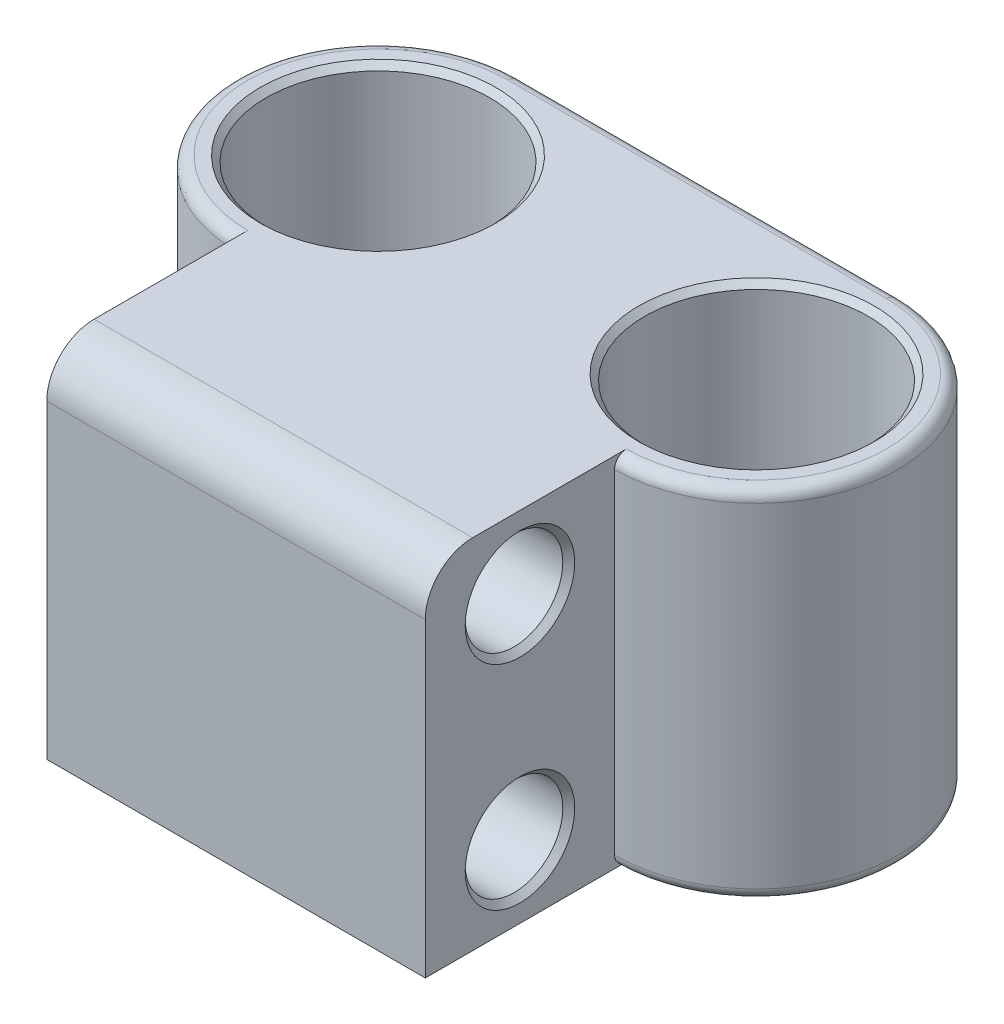
SolidWorks part; units mm, degrees
ref_plane "Front Plane" through (0, 0, 0) normal (0, 0, 1) x (1, 0, 0)
ref_plane "Top Plane" through (0, 0, 0) normal (0, 1, 0) x (1, 0, 0)
ref_plane "Right Plane" through (0, 0, 0) normal (1, 0, 0) x (0, 0, -1)
sketch "Sketch1" plane through (0, 0, 0) normal (0, 1, 0) x (1, 0, 0)
  line L0 (-12.7, 15.875) -> (12.7, 15.875) construction
  line L1 (12.7, -6.35) -> (-12.7, -6.35)
  line L2 (12.7, -6.35) -> (12.7, 6.35)
  line L4 (-12.7, -6.35) -> (-12.7, 6.35)
  line L5 (12.7, -6.35) -> (-12.7, 6.35) construction
  line L6 (12.7, 6.35) -> (-12.7, -6.35) construction
  line L7 (0, 15.875) -> (0, 0) construction
  line L9 (12.7, 25.4) -> (-12.7, 25.4)
  circle A0 centre (-12.7, 15.875) radius 7.5
  arc A1 (-12.7, 25.4) -> (-12.7, 6.35) centre (-12.7, 15.875) ccw
  circle A2 centre (12.7, 15.875) radius 7.5
  arc A3 (12.7, 25.4) -> (12.7, 6.35) centre (12.7, 15.875) cw
  point P0 (0, 0)
  dimension "D3" = 15
  dimension "D1" = 12.7
  dimension "D2" = 25.4
  dimension "D4" = 25.4
  dimension "D5" = 15.875
  dimension "D6" = 25.4
extrude "Boss-Extrude1" add sketch "Sketch1" along normal blind 24
fillet "Fillet1" [suppressed] radius 3.175
chamfer "Chamfer1" distance 0.4 angle 45 4 edges at (12.7, 0, -23.375) (-12.7, 0, -8.375) (-12.7, 24, -8.375) (12.7, 24, -23.375)
fillet "Fillet2" radius 3.175 1 edges at (0, 24, 6.35)
sketch "Sketch2" plane through (12.7, 0, 0) normal (1, 0, 0) x (0, 0, -1)
  line L0 (0, 0) -> (0, 24) construction
  line L1 (-6.35, 0) -> (6.35, 0) construction
  line L2 (-3.175, 24) -> (6.35, 24) construction
  line L3 (6.35, 12) -> (-6.35, 12) construction
  line L4 (6.35, 24) -> (6.35, 0) construction
  line L5 (-6.35, 20.825) -> (-6.35, 0) construction
  circle A0 centre (0, 19.1438) radius 3.275
  circle A1 centre (0, 4.8562) radius 3.275
  dimension "D1" = 6.55
  dimension "D2" = 7.1437
extrude "Cut-Extrude1" cut sketch "Sketch2" against normal through all
chamfer "Chamfer2" distance 0.4 angle 45 4 edges at (12.7, 4.8562, 3.275) (12.7, 19.1438, -3.275) (-12.7, 19.1438, -3.275) (-12.7, 4.8562, -3.275)
fillet "Fillet3" radius 0.7937 6 edges at (-22.225, 24, -15.875) (0, 24, -25.4) (-22.225, 0, -15.875) (0, 0, -25.4) (22.225, 24, -15.875) (22.225, 0, -15.875)
